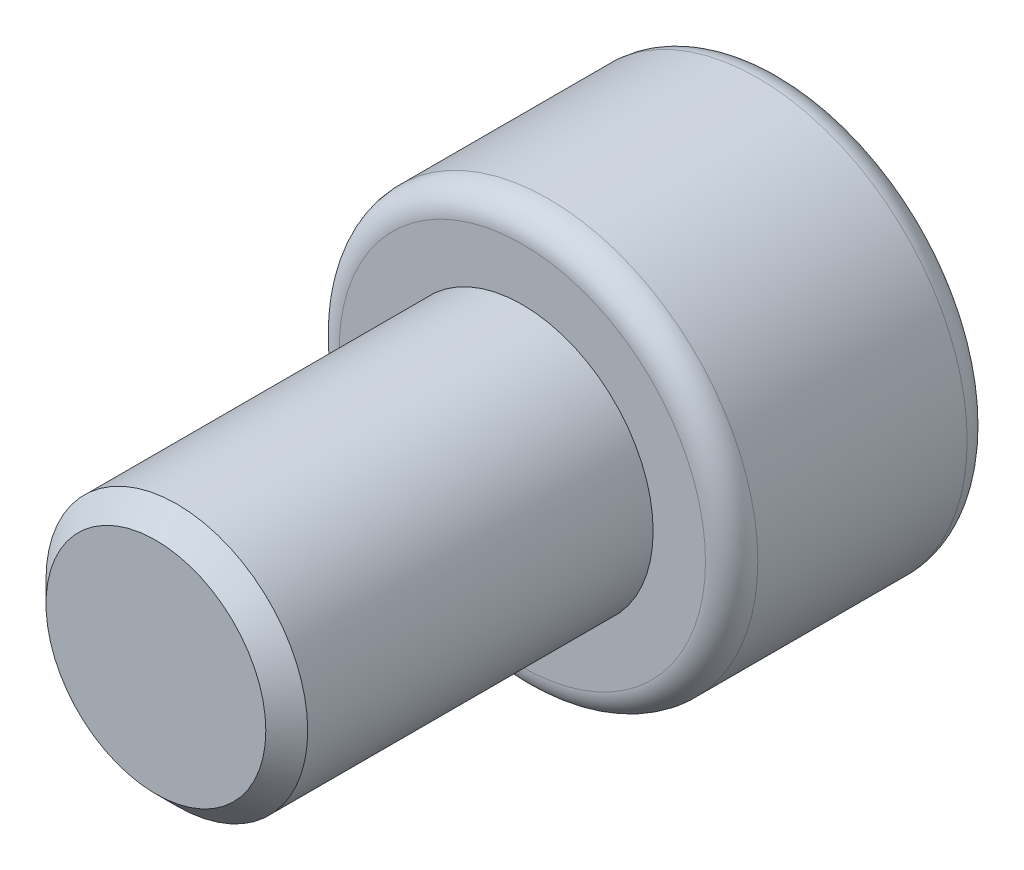
SolidWorks part; units mm, degrees
ref_plane "Plano frontal" through (0, 0, 0) normal (0, 0, 1) x (1, 0, 0)
ref_plane "Plano superior" through (0, 0, 0) normal (0, 1, 0) x (1, 0, 0)
ref_plane "Plano direito" through (0, 0, 0) normal (1, 0, 0) x (0, 0, -1)
sketch "Esboço1" plane through (0, 0, 0) normal (0, 0, 1) x (1, 0, 0)
  circle A0 centre (0, 0) radius 4
  dimension "D1" = 8
extrude "Ressalto-extrusão1" add sketch "Esboço1" along normal blind 5 contours A0
sketch "Esboço2" plane through (0, 0, 5) normal (0, 0, 1) x (1, 0, 0)
  circle A0 centre (0, 0) radius 2.5
  dimension "D1" = 5
extrude "Ressalto-extrusão2" add sketch "Esboço2" along normal blind 7
sketch "Esboço3" plane through (0, 0, 0) normal (0, 0, -1) x (-1, 0, 0)
  line L1 (0, 2.3094) -> (-2, 1.1547)
  line L2 (-2, 1.1547) -> (-2, -1.1547)
  line L3 (-2, -1.1547) -> (0, -2.3094)
  line L4 (0, -2.3094) -> (2, -1.1547)
  line L5 (2, -1.1547) -> (2, 1.1547)
  line L6 (2, 1.1547) -> (0, 2.3094)
  circle A0 centre (0, 0) radius 2 construction
  dimension "D1" = 4
extrude "Corte-extrusão1" cut sketch "Esboço3" against normal blind 3
fillet "Filete1" radius 0.5 2 edges at (4, 0, 5) (4, 0, 0)
fillet "Filete2" radius 0.2 6 edges at (-1, -1.7321, 0) (1, -1.7321, 0) (-2, 0, 0) (-1, 1.7321, 0) (1, 1.7321, 0) (2, 0, 0)
chamfer "Chanfro2" distance 0.4 angle 45 1 edges at (2.5, 0, 12)
